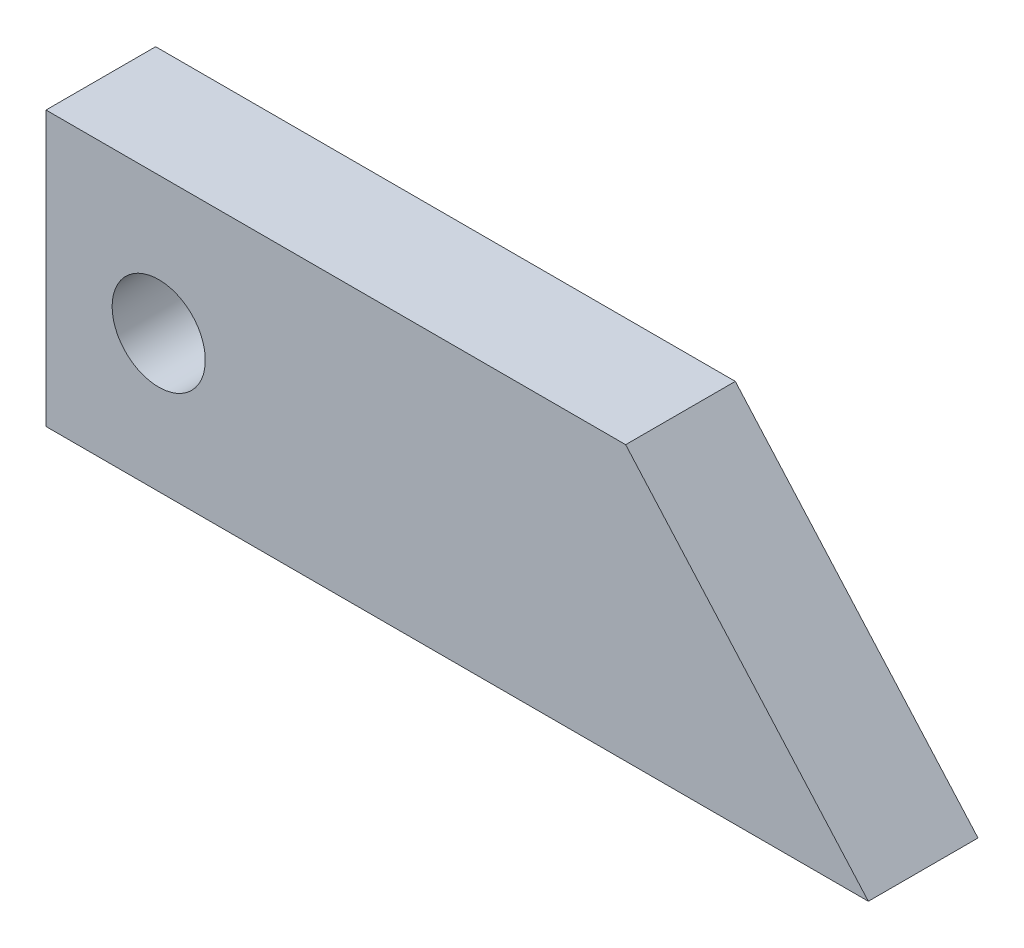
SolidWorks part; units mm, degrees
ref_plane "Plan de face" through (0, 0, 0) normal (0, 0, 1) x (1, 0, 0)
ref_plane "Plan de dessus" through (0, 0, 0) normal (0, 1, 0) x (1, 0, 0)
ref_plane "Plan de droite" through (0, 0, 0) normal (1, 0, 0) x (0, 0, -1)
sketch "Esquisse1" plane through (0, 0, 0) normal (0, 0, 1) x (1, 0, 0)
  line L0 (0, 0) -> (0, 10)
  line L1 (0, 10) -> (21.1466, 10)
  line L2 (21.1466, 10) -> (30, 0)
  line L3 (30, 0) -> (0, 0)
  dimension "D1" = 10
  dimension "D2" = 30
extrude "Extrusion1" add sketch "Esquisse1" along normal blind 4
hole_wizard "Fraisage pour vis à tête fraisée M31" positions "Esquisse3D1" profile "Esquisse2" countersink size "M3" standard "ISO" end condition through all
sketch3d "Esquisse3D1"
  line L2 (3.952, 0, 0) -> (4.2717, 10, 0) construction
  line L3 (0, 0, 0) -> (30, 0, 0) construction
  line L4 (21.1466, 10, 0) -> (0, 10, 0) construction
  point P0 (4.1118, 5, 0)
sketch "Esquisse2" plane through (4.1118, 5, 0) normal (1, 0, 0) x (0, 1, 0)
  line L0 (0, 0) -> (0, 4)
  line L1 (0, 4) -> (1.7, 4)
  line L2 (1.7, 4) -> (1.7, 1.45)
  line L3 (1.7, 1.45) -> (3.15, 0)
  line L5 (3.15, 0) -> (0, 0)
  line L6 (-1.7, 1.45) -> (-3.15, 0) construction
  line L11 (0, -6.35) -> (0, 107.95) construction
  dimension "Diamètre du perçage jusqu'au prochain" = 3.4
  dimension "Profondeur du perçage jusqu'au prochain" = 4
  dimension "Diamètre du fraisage entrant" = 6.3
  dimension "Angle du fraisage entrant" = 90
